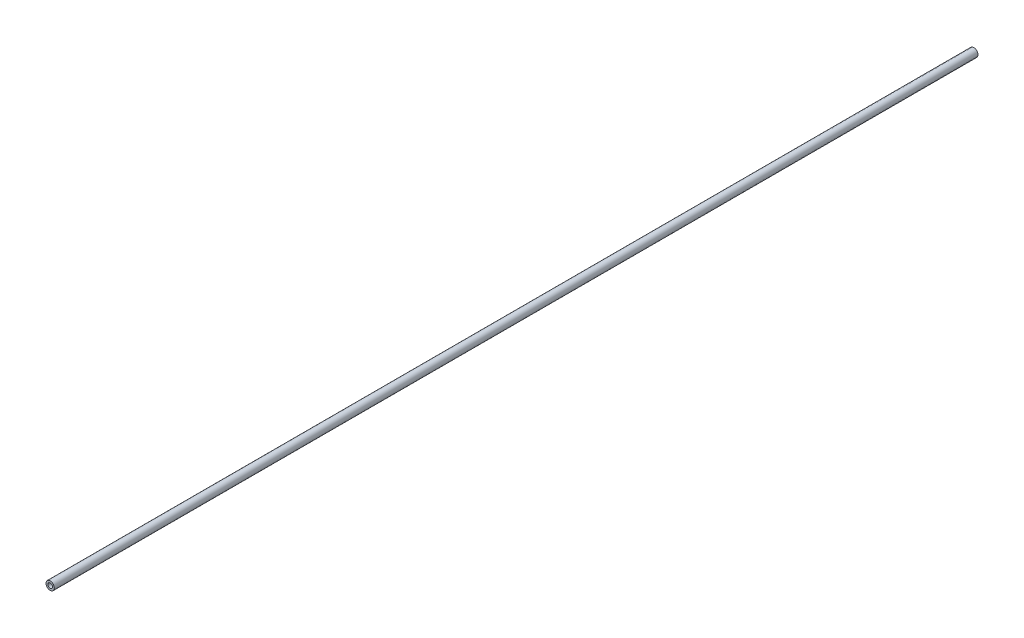
SolidWorks part; units mm, degrees
ref_plane "Front Plane" through (0, 0, 0) normal (0, 0, 1) x (1, 0, 0)
ref_plane "Top Plane" through (0, 0, 0) normal (0, 1, 0) x (1, 0, 0)
ref_plane "Right Plane" through (0, 0, 0) normal (1, 0, 0) x (0, 0, -1)
sketch "Sketch1" plane through (0, 0, 0) normal (0, 0, 1) x (1, 0, 0)
  circle A0 centre (0, 0) radius 6.858
  dimension "Pipe OD" = 13.716
extrude "Extrude-Thin1" add sketch "Sketch1" along normal mid plane 1524 thin thin type one direction reverse wall 3.0226
